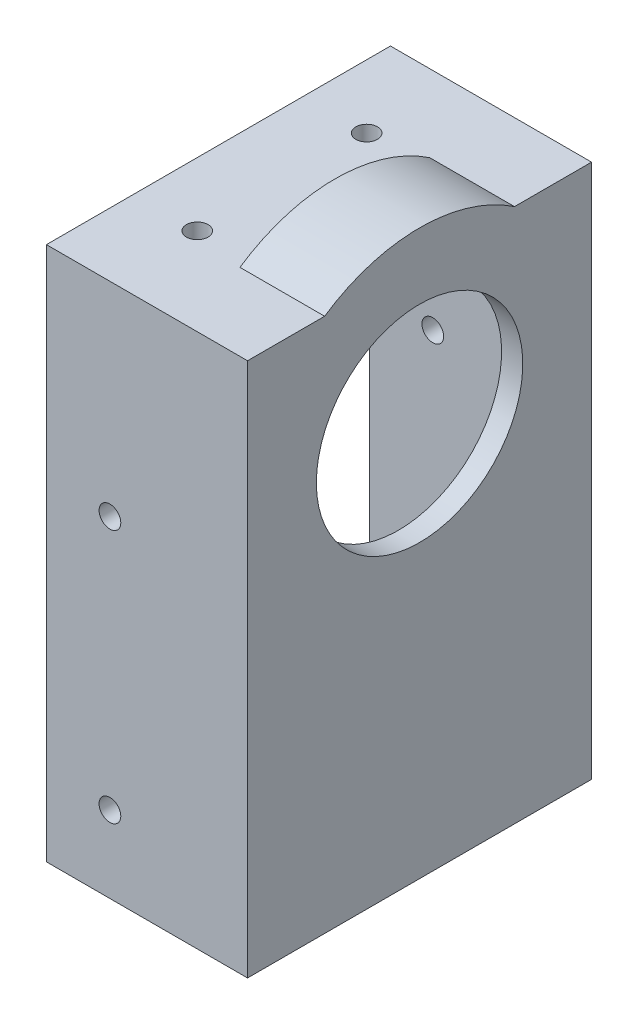
SolidWorks part; units mm, degrees
ref_plane "정면" through (0, 0, 0) normal (0, 0, 1) x (1, 0, 0)
ref_plane "윗면" through (0, 0, 0) normal (0, 1, 0) x (1, 0, 0)
ref_plane "우측면" through (0, 0, 0) normal (1, 0, 0) x (0, 0, -1)
sketch "Sketch1" plane through (0, 0, 0) normal (1, 0, 0) x (0, 0, -1)
  line L1 (0, 0) -> (28.5, 0)
  line L2 (0, 0) -> (0, 46.5)
  line L3 (0, 46.5) -> (28.5, 46.5)
  line L4 (28.5, 0) -> (28.5, 46.5)
  dimension "D1" = 28.5
  dimension "D2" = 46.5
extrude "Extrude-Thin1" add sketch "Sketch1" along normal blind 17 thin
sketch "Sketch2" plane through (0, 0, 2) normal (0, 0, 1) x (1, 0, 0)
  line L0 (0, 23.25) -> (26.4565, 23.25) construction
  line L1 (0, 48.5) -> (0, -2) construction
  line L2 (17, 48.5) -> (17, -2) construction
  line L3 (17, -2) -> (0, -2) construction
  point P0 (6, 5.25)
  point P1 (6, 29.25)
  dimension "D1" = 24
  dimension "D2" = 11
  dimension "D3" = 31.25
hole_wizard "Tap Drill for M2.5 Tap1" positions "3DSketch1" profile "Sketch3" hole size "M2.5" standard "KS" end condition through all
sketch3d "3DSketch1"
  point P0 (6, 29.25, 2)
  point P3 (6, 5.25, 2)
sketch "Sketch3" plane through (6, 29.25, 2) normal (1, 0, 0) x (0, -1, 0)
  line L0 (0, 0) -> (0, 32.5)
  line L1 (0, 32.5) -> (1.025, 32.5)
  line L2 (1.025, 32.5) -> (1.025, 0)
  line L5 (1.025, 0) -> (0, 0)
  line L11 (0, -6.35) -> (0, 107.95) construction
  dimension "Thru Hole Dia." = 2.05
  dimension "Thru Hole Depth" = 32.5
sketch "Sketch5" plane through (0, 48.5, 0) normal (0, 1, 0) x (1, 0, 0)
  line L0 (0, 14.25) -> (23.4315, 14.25) construction
  line L1 (0, 30.5) -> (0, -2) construction
  line L2 (17, 30.5) -> (17, -2) construction
  point P0 (6, 22.25)
  point P1 (6, 6.25)
  dimension "D1" = 16
  dimension "D2" = 11
  dimension "D3" = 8
hole_wizard "Tap Drill for M2.5 Tap2" positions "3DSketch2" profile "Sketch6" hole size "M2.5" standard "KS" end condition through all
sketch3d "3DSketch2"
  point P0 (6, 48.5, -6.25)
  point P3 (6, 48.5, -22.25)
sketch "Sketch6" plane through (6, 48.5, -6.25) normal (1, 0, 0) x (0, 0, 1)
  line L0 (0, 0) -> (0, 50.5)
  line L1 (0, 50.5) -> (1.025, 50.5)
  line L2 (1.025, 50.5) -> (1.025, 0)
  line L5 (1.025, 0) -> (0, 0)
  line L11 (0, -6.35) -> (0, 107.95) construction
  dimension "Thru Hole Dia." = 2.05
  dimension "Thru Hole Depth" = 50.5
ref_plane "Plane1" through (17, 0, 0) normal (1, 0, 0) x (0, 0, -1)
sketch "Sketch7" plane through (17, 0, 0) normal (1, 0, 0) x (0, 0, -1)
  line L5 (-2, -2) -> (30.5, -2)
  line L6 (-2, -2) -> (-2, 48.5)
  line L7 (-2, 48.5) -> (30.5, 48.5)
  line L8 (30.5, -2) -> (30.5, 48.5)
extrude "Boss-Extrude1" add sketch "Sketch7" along normal blind 2
sketch "Sketch9" plane through (17, 0, 0) normal (-1, 0, 0) x (0, 0, 1)
  line L0 (-14.25, 0) -> (-14.25, 46.5) construction
  line L1 (0, 0) -> (-28.5, 0) construction
  line L2 (-28.5, 46.5) -> (0, 46.5) construction
  line L3 (-28.5, 46.5) -> (0, 46.5) construction
  circle A0 centre (-14.25, 35.25) radius 9.75
  dimension "D1" = 11.25
  dimension "D2" = 19.5
extrude "Cut-Extrude1" cut sketch "Sketch9" against normal blind 2
sketch "Sketch10" plane through (19, 0, 0) normal (1, 0, 0) x (0, 0, -1)
  line L0 (5.2813, 48.5) -> (23.2187, 48.5)
  arc A0 (23.2187, 48.5) -> (5.2813, 48.5) centre (14.25, 35.25) ccw
extrude "Boss-Extrude2" add sketch "Sketch10" against normal blind 8
